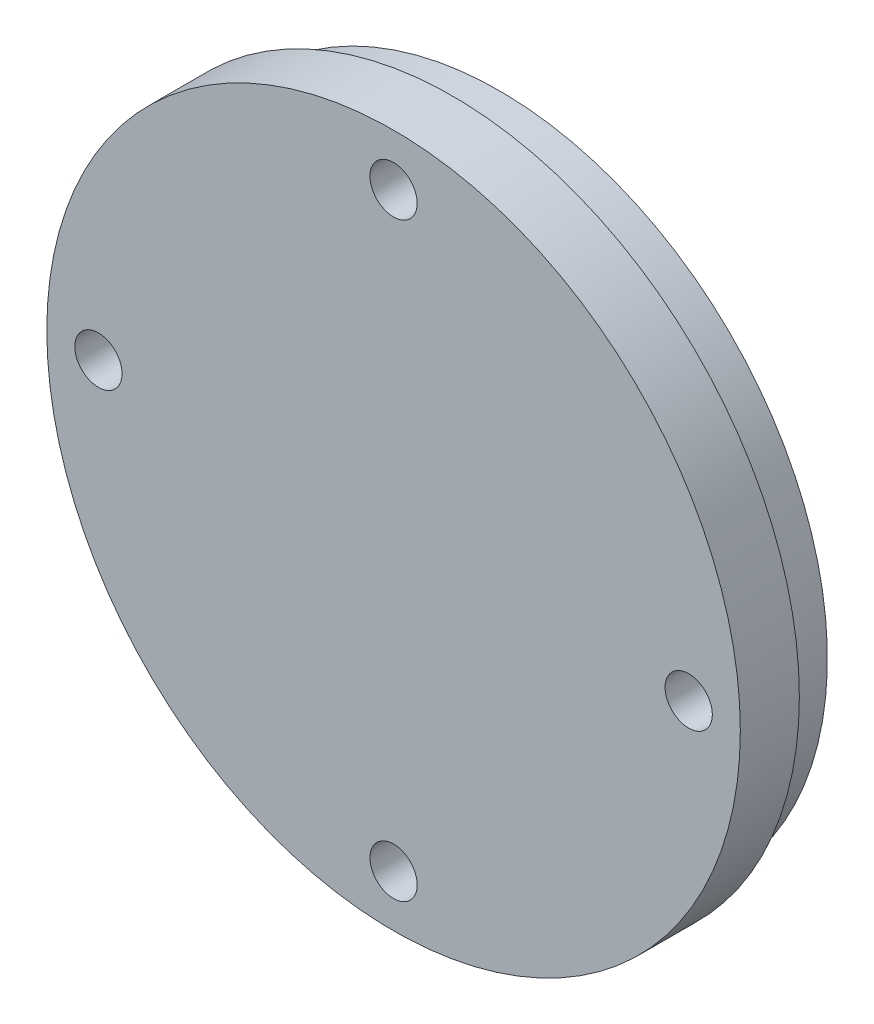
SolidWorks part; units mm, degrees
material "ABS"
ref_plane "正面" through (0, 0, 0) normal (0, 0, 1) x (1, 0, 0)
ref_plane "平面" through (0, 0, 0) normal (0, 1, 0) x (1, 0, 0)
ref_plane "右側面" through (0, 0, 0) normal (1, 0, 0) x (0, 0, -1)
sketch "ｽｹｯﾁ1" plane through (0, 0, 0) normal (0, 0, 1) x (1, 0, 0)
  circle A0 centre (0, 0) radius 23.5
  dimension "D1" = 47
extrude "ﾎﾞｽ - 押し出し1" add sketch "ｽｹｯﾁ1" along normal blind 4
sketch "ｽｹｯﾁ2" plane through (0, 0, 0) normal (0, 0, -1) x (-1, 0, 0)
  circle A0 centre (0, 0) radius 22.225
  dimension "D1" = 44.45
extrude "ﾎﾞｽ - 押し出し2" add sketch "ｽｹｯﾁ2" along normal blind 3.175
sketch "ｽｹｯﾁ3" plane through (0, 0, -3.175) normal (0, 0, -1) x (-1, 0, 0)
  circle A0 centre (0, 0) radius 20 construction
  circle A1 centre (0, 20) radius 1.6
  circle A2 centre (20, 0) radius 1.6
  circle A3 centre (0, -20) radius 1.6
  circle A4 centre (-20, 0) radius 1.6
  point P14 (0, 0)
  dimension "D1" = 40
  dimension "D2" = 3.2
  dimension "D3" = 4
extrude "ｶｯﾄ - 押し出し1" cut sketch "ｽｹｯﾁ3" against normal through all
